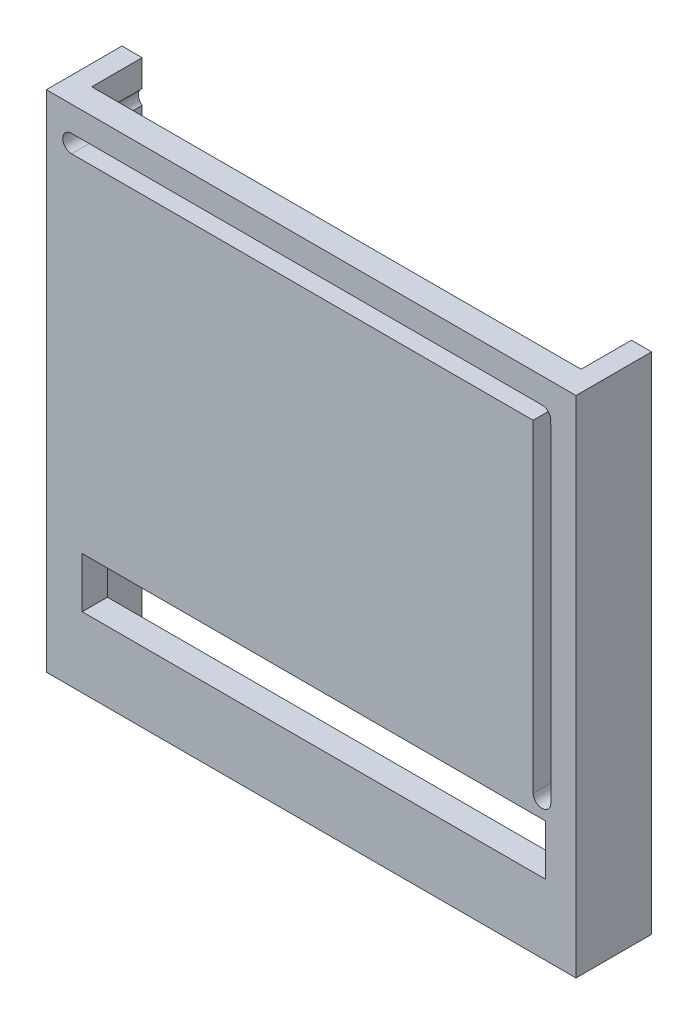
SolidWorks part; units mm, degrees
material "Balsa"
ref_plane "Plan de face" through (0, 0, 0) normal (0, 0, 1) x (1, 0, 0)
ref_plane "Plan de dessus" through (0, 0, 0) normal (0, 1, 0) x (1, 0, 0)
ref_plane "Plan de droite" through (0, 0, 0) normal (1, 0, 0) x (0, 0, -1)
sketch "Sketch1" plane through (0, 0, 0) normal (0, 0, 1) x (1, 0, 0)
  line L1 (-105, -100) -> (105, -100)
  line L2 (-105, -100) -> (-105, 100)
  line L3 (-105, 100) -> (105, 100)
  line L4 (105, -100) -> (105, 100)
  line L5 (-105, -100) -> (105, 100) construction
  line L6 (-105, 100) -> (105, -100) construction
  point P0 (0, 0)
  dimension "D1" = 210
  dimension "D2" = 200
extrude "Boss-Extrude1" add sketch "Sketch1" along normal blind 30
sketch "Sketch2" plane through (0, -100, 0) normal (0, -1, 0) x (-1, 0, 0)
  line L0 (105, 0) -> (-105, 0) construction
  line L1 (97, 0) -> (-97, 0)
  line L2 (97, 0) -> (97, -20)
  line L3 (97, -20) -> (-97, -20)
  line L4 (-97, 0) -> (-97, -20)
  line L5 (97, 0) -> (-97, -20) construction
  line L6 (97, -20) -> (-97, 0) construction
  line L7 (105, -30) -> (105, 0) construction
  line L8 (-105, -30) -> (-105, 0) construction
  point P0 (0, -10)
  dimension "D1" = 20
  dimension "D2" = 8
  dimension "D3" = 8
extrude "Cut-Extrude1" cut sketch "Sketch2" against normal through all
sketch "Sketch3" plane through (0, 0, 30) normal (0, 0, 1) x (1, 0, 0)
  line L0 (88, 85) -> (88, -45)
  line L1 (95, 85) -> (95, -45)
  line L2 (105, -100) -> (105, 100) construction
  line L3 (105, 100) -> (-105, 100) construction
  line L4 (-105, -100) -> (105, -100) construction
  arc A0 (95, 85) -> (88, 85) centre (91.5, 85) ccw
  arc A1 (95, -45) -> (88, -45) centre (91.5, -45) cw
  dimension "D3" = 15
  dimension "D1" = 10
  dimension "D2" = 7
  dimension "D4" = 55
extrude "Cut-Extrude2" cut sketch "Sketch3" against normal through all
sketch "Sketch4" plane through (0, 0, 30) normal (0, 0, 1) x (1, 0, 0)
  line L0 (91.5, 83) -> (-95, 83)
  line L1 (91.5, 90) -> (-95, 90)
  line L2 (105, 100) -> (-105, 100) construction
  line L3 (-105, 100) -> (-105, -100) construction
  line L4 (105, -100) -> (105, 100) construction
  arc A0 (91.5, 83) -> (91.5, 90) centre (91.5, 86.5) ccw
  arc A1 (-95, 83) -> (-95, 90) centre (-95, 86.5) cw
  dimension "D1" = 10
  dimension "D2" = 7
  dimension "D3" = 10
  dimension "D4" = 13.5
extrude "Cut-Extrude3" cut sketch "Sketch4" against normal through all
sketch "Sketch5" plane through (0, -100, 0) normal (0, -1, 0) x (-1, 0, 0)
  line L0 (90, -27) -> (-90, -27)
  line L1 (90, -22) -> (-90, -22)
  line L2 (105, -30) -> (-105, -30) construction
  line L3 (105, -30) -> (105, 0) construction
  line L4 (-105, -30) -> (-105, 0) construction
  arc A0 (90, -27) -> (90, -22) centre (90, -24.5) ccw
  arc A1 (-90, -27) -> (-90, -22) centre (-90, -24.5) cw
  dimension "D1" = 5
  dimension "D2" = 3
  dimension "D3" = 15
  dimension "D4" = 15
sketch "Sketch6" plane through (0, 0, 20) normal (0, 0, -1) x (-1, 0, 0)
  line L1 (90.7668, -72.139) -> (-92.9321, -72.139)
  line L2 (90.7668, -72.139) -> (90.7668, -52.139)
  line L3 (90.7668, -52.139) -> (-92.9321, -52.139)
  line L4 (-92.9321, -72.139) -> (-92.9321, -52.139)
  dimension "D1" = 20
extrude "Cut-Extrude4" cut sketch "Sketch6" against normal through all
extrude "Cut-Extrude6" cut sketch "Sketch5" against normal blind 5
